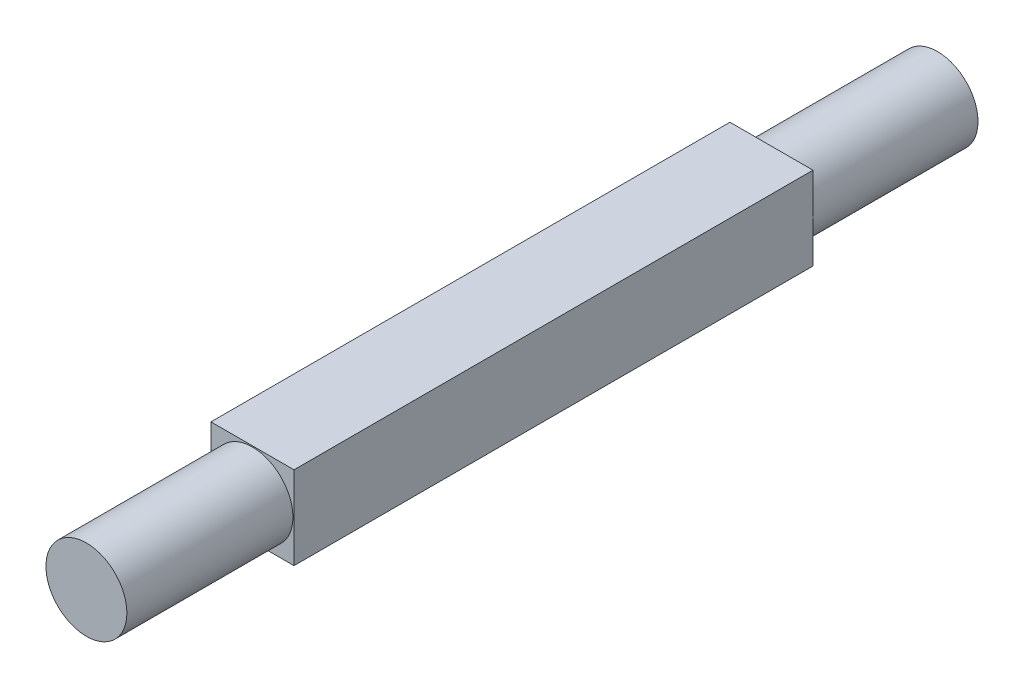
SolidWorks part; units mm, degrees
ref_plane "Front Plane" through (0, 0, 0) normal (0, 0, 1) x (1, 0, 0)
ref_plane "Top Plane" through (0, 0, 0) normal (0, 1, 0) x (1, 0, 0)
ref_plane "Right Plane" through (0, 0, 0) normal (1, 0, 0) x (0, 0, -1)
sketch "Sketch1" plane through (0, 0, 0) normal (0, 0, 1) x (1, 0, 0)
  line L1 (2, -2) -> (-2, -2)
  line L2 (2, -2) -> (2, 2)
  line L3 (2, 2) -> (-2, 2)
  line L4 (-2, -2) -> (-2, 2)
  line L5 (2, -2) -> (-2, 2) construction
  line L6 (2, 2) -> (-2, -2) construction
  dimension "D2" = 4
extrude "Boss-Extrude1" add sketch "Sketch1" along normal mid plane 25
sketch "Sketch2" plane through (0, 0, 12.5) normal (0, 0, 1) x (1, 0, 0)
  circle A0 centre (0, 0) radius 1.95
  dimension "D1" = 3.9
extrude "Boss-Extrude2" add sketch "Sketch2" along normal blind 8
mirror "Mirror2" about plane through (0, 0, 0) normal (0, 0, 1) of "Boss-Extrude2"
